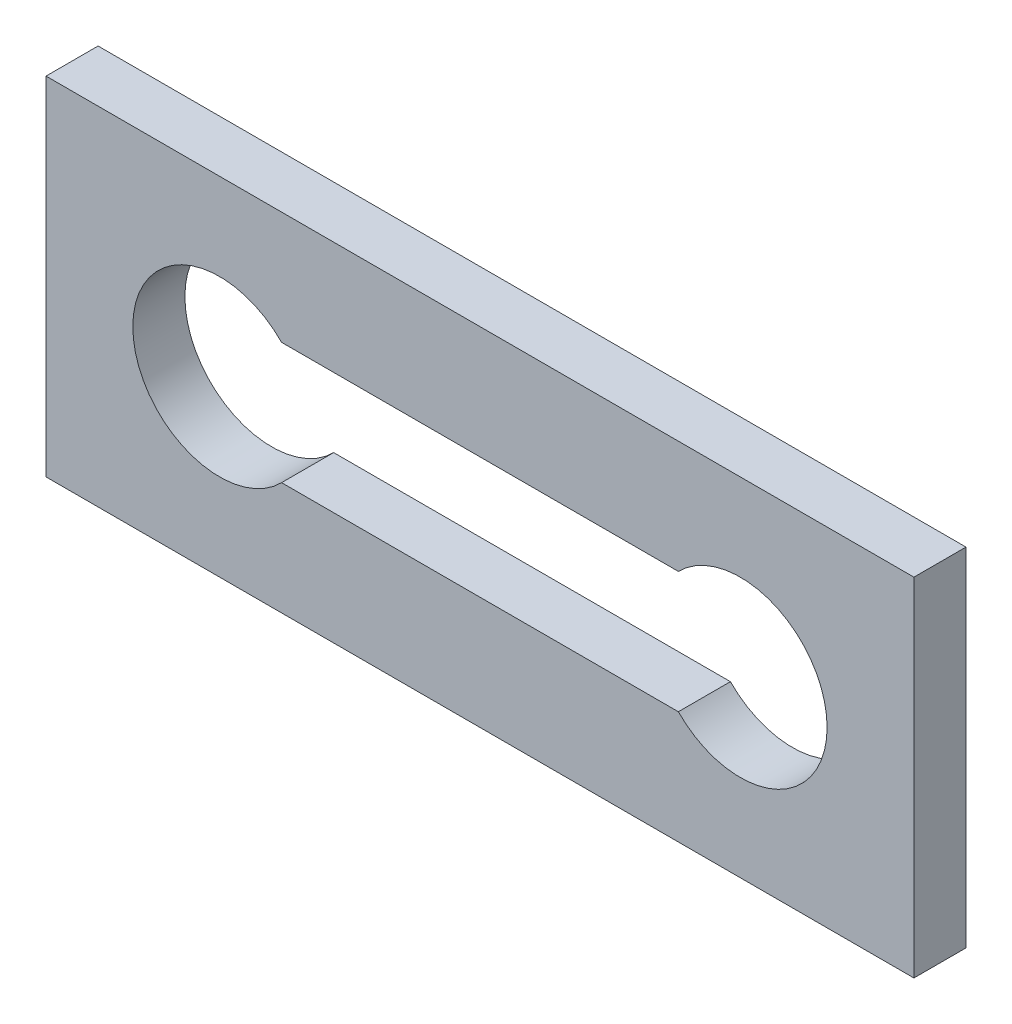
SolidWorks part; units mm, degrees
ref_plane "정면" through (0, 0, 0) normal (0, 0, 1) x (1, 0, 0)
ref_plane "윗면" through (0, 0, 0) normal (0, 1, 0) x (1, 0, 0)
ref_plane "우측면" through (0, 0, 0) normal (1, 0, 0) x (0, 0, -1)
sketch "스케치1" plane through (0, 0, 0) normal (0, 0, 1) x (1, 0, 0)
  line L1 (-25, -10) -> (25, -10)
  line L2 (-25, -10) -> (-25, 10)
  line L3 (-25, 10) -> (25, 10)
  line L4 (25, -10) -> (25, 10)
  line L5 (-25, -10) -> (25, 10) construction
  line L6 (-25, 10) -> (25, -10) construction
  line L7 (-15, -3.5) -> (15, -3.5)
  line L8 (-15, -3.5) -> (-15, 3.5)
  line L9 (-15, 3.5) -> (15, 3.5)
  line L10 (15, -3.5) -> (15, 3.5)
  line L11 (-15, -3.5) -> (15, 3.5) construction
  line L12 (-15, 3.5) -> (15, -3.5) construction
  circle A0 centre (-15, 0) radius 6.5181
  circle A1 centre (15, 0) radius 5
  point P0 (0, 0)
  point P6 (0, 0)
  dimension "D5" = 10
  dimension "D6" = 13.0362
  dimension "D1" = 50
  dimension "D2" = 20
  dimension "D3" = 7
  dimension "D4" = 30
extrude "보스-돌출1" add sketch "스케치1" along normal blind 3 contours L2 L1 L4 L3
sketch "스케치2" plane through (0, 0, 3) normal (0, 0, 1) x (1, 0, 0)
  line L1 (-15, -3.5) -> (15, -3.5)
  line L2 (-15, -3.5) -> (-15, 3.5)
  line L3 (-15, 3.5) -> (15, 3.5)
  line L4 (15, -3.5) -> (15, 3.5)
  line L5 (-15, -3.5) -> (15, 3.5) construction
  line L6 (-15, 3.5) -> (15, -3.5) construction
  circle A0 centre (-15, 0) radius 5
  circle A1 centre (15, 0) radius 5
  point P0 (0, 0)
  dimension "D3" = 10
  dimension "D4" = 10
  dimension "D1" = 30
  dimension "D2" = 7
extrude "컷-돌출1" cut sketch "스케치2" against normal blind 3 contours A0 | L3 L4 L1 L2 | A1
